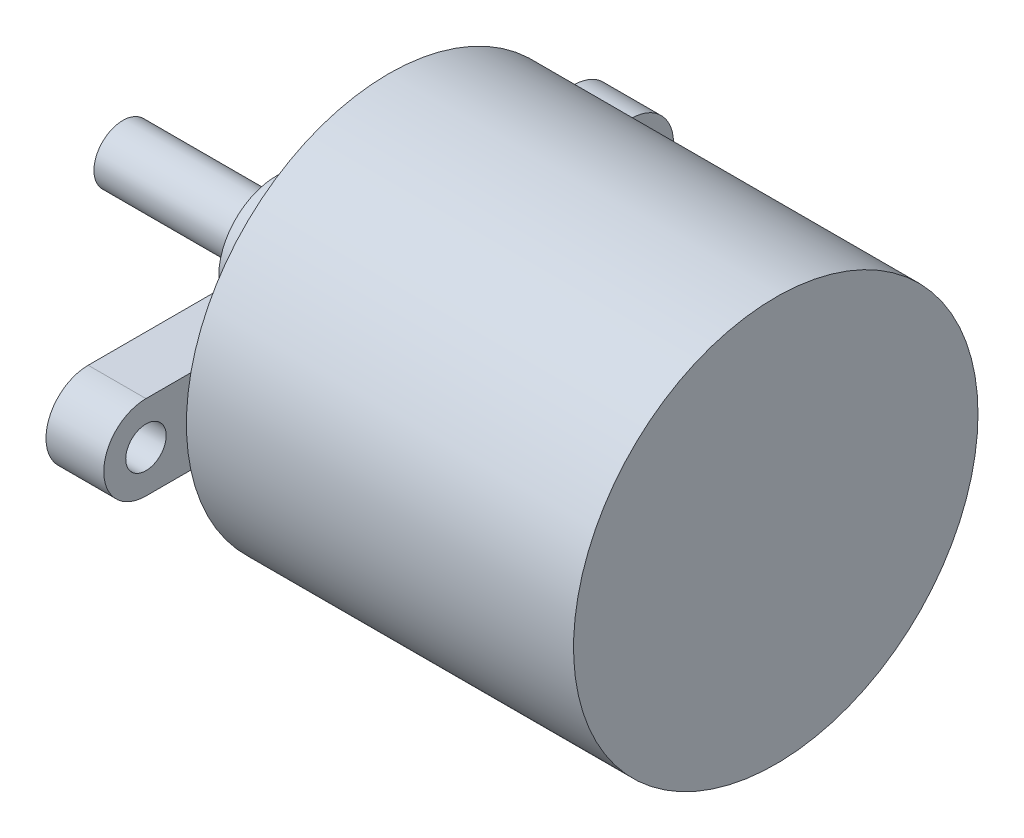
SolidWorks part; units mm, degrees
material "ABS"
ref_plane "Front" through (0, 0, 0) normal (0, 0, 1) x (1, 0, 0)
ref_plane "Top" through (0, 0, 0) normal (0, 1, 0) x (1, 0, 0)
ref_plane "Right" through (0, 0, 0) normal (1, 0, 0) x (0, 0, -1)
sketch "Sketch1" plane through (0, 0, 0) normal (1, 0, 0) x (0, 0, -1)
  circle A0 centre (0, 0) radius 17.5
  dimension "D1" = 35
extrude "Boss-Extrude1" add sketch "Sketch1" along normal blind 33.5
sketch "Sketch2" plane through (0, 0, 0) normal (-1, 0, 0) x (0, 0, 1)
  line L0 (-21, 0) -> (21, 0) construction
  line L1 (-21, 3.65) -> (21, 3.65)
  line L2 (-21, -3.65) -> (21, -3.65)
  arc A0 (-21, 3.65) -> (-21, -3.65) centre (-21, 0) ccw
  arc A1 (21, -3.65) -> (21, 3.65) centre (21, 0) ccw
  point P2 (0, 0)
  dimension "D1" = 3.65
  dimension "D2" = 42
extrude "Boss-Extrude2" add sketch "Sketch2" along normal blind 5
hole_wizard "Ø3.5 (3.5) Diameter Hole1" positions "Sketch4" profile "Sketch3" hole size "Ø3.5" standard "ANSI Metric"
sketch "Sketch4" plane through (-5, 0, 0) normal (-1, 0, 0) x (0, 0, 1)
  arc A0 (-21, 3.65) -> (-21, -3.65) centre (-21, 0) ccw construction
  arc A1 (21, -3.65) -> (21, 3.65) centre (21, 0) ccw construction
  point P0 (-21, -0.1403)
  point P1 (21, 0)
  dimension "D1" = 0
  dimension "D2" = 0
sketch "Sketch3" plane through (-5, -0.1403, -21) normal (0, 1, 0) x (0, 0, 1)
  line L0 (0, 0) -> (0, 71.0515)
  line L1 (0, 71.0515) -> (1.75, 70)
  line L2 (1.75, 70) -> (1.75, 0)
  line L5 (1.75, 0) -> (0, 0)
  line L10 (0, 71.0515) -> (-1.75, 70) construction
  line L11 (0, -6.35) -> (0, 107.95) construction
  dimension "Hole Dia." = 3.5
  dimension "Hole Depth" = 70
  dimension "Drill Angle" = 118
sketch "Sketch5" plane through (-5, 0, 0) normal (-1, 0, 0) x (0, 0, 1)
  circle A0 centre (0, 0) radius 5
  dimension "D1" = 10
extrude "Boss-Extrude3" add sketch "Sketch5" along normal blind 4.7
sketch "Sketch6" plane through (-9.7, 0, 0) normal (-1, 0, 0) x (0, 0, 1)
  circle A0 centre (0, 0) radius 2.5
  dimension "D1" = 5
extrude "Boss-Extrude4" add sketch "Sketch6" along normal blind 13.3
